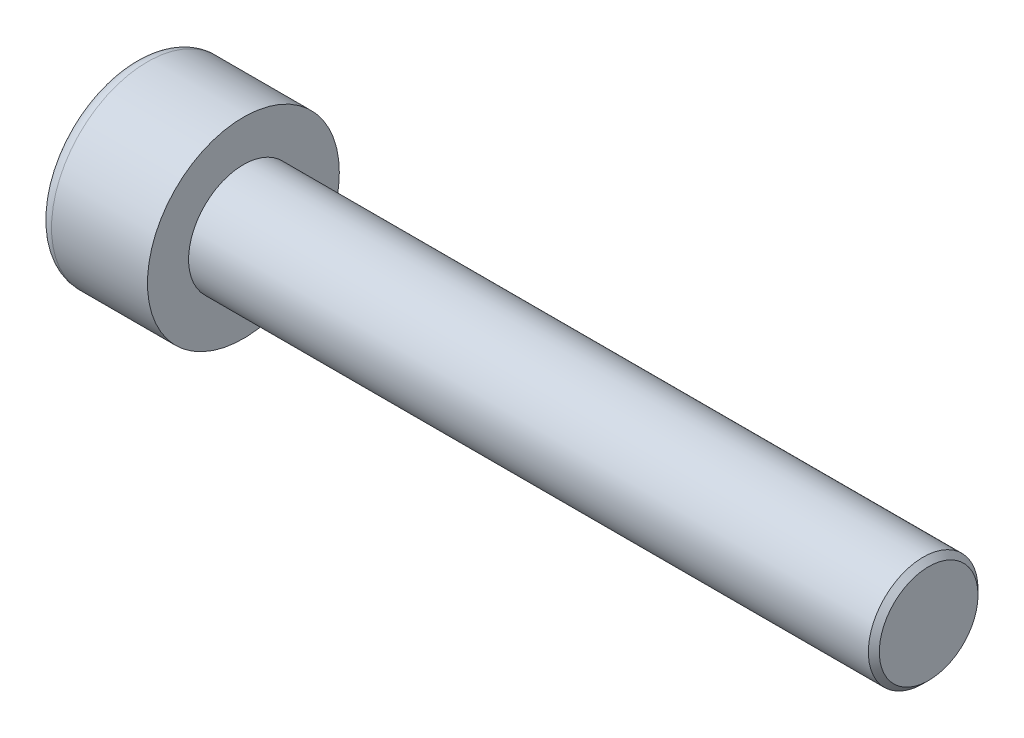
SolidWorks part; units mm, degrees
ref_plane "Front" through (0, 0, 0) normal (0, 0, 1) x (1, 0, 0)
ref_plane "Top" through (0, 0, 0) normal (0, 1, 0) x (1, 0, 0)
ref_plane "Right" through (0, 0, 0) normal (1, 0, 0) x (0, 0, -1)
sketch "Sketch1" plane through (0, 0, 0) normal (1, 0, 0) x (0, 0, -1)
  circle A0 centre (0, 0) radius 3.5
  dimension "dk" = 7
extrude "BaseHead" add sketch "Sketch1" along normal blind 4
sketch "Sketch2" plane through (4, 0, 0) normal (1, 0, 0) x (0, 0, -1)
  circle A0 centre (0, 0) radius 2
  dimension "d" = 4
extrude "BaseBody" add sketch "Sketch2" along normal blind 25
cosmetic thread "ThreadCosmetic1" parameters "b"=25, "D2"=3.242
sketch "Sketch3" plane through (0, 0, 0) normal (1, 0, 0) x (0, 0, -1)
  line L1 (1.7321, 0) -> (0.866, 1.5)
  line L2 (0.866, 1.5) -> (-0.866, 1.5)
  line L3 (-0.866, 1.5) -> (-1.7321, 0)
  line L4 (-1.7321, 0) -> (-0.866, -1.5)
  line L5 (-0.866, -1.5) -> (0.866, -1.5)
  line L6 (0.866, -1.5) -> (1.7321, 0)
  circle A0 centre (0, 0) radius 1.5 construction
  dimension "s" = 3
  dimension "e" = 3.4641
extrude "HexagonSocket" cut sketch "Sketch3" along normal blind 2
sketch "Sketch4" plane through (-4.1961, 0.75, 0) normal (0, 0, 1) x (-1, 0, 0)
  line L0 (-6.1961, 2.25) -> (-7.0622, 0.75)
  line L2 (-7.0622, 0.75) -> (-6.1961, 0.75)
  line L3 (-6.1961, 0.75) -> (-6.1961, 2.25)
  line L4 (-5.0351, 0.75) -> (0.839, 0.75) construction
  line L5 (-33.1961, 0.75) -> (-8.1961, 0.75) construction
  line L6 (-8.1961, 0.75) -> (-4.1961, 0.75) construction
  dimension "m" = 60
revolve "Cut-Revolve1" cut sketch "Sketch4" angle 360 about L4
fillet "HeadFillet" [suppressed] radius 0.2
fillet "TopFillet" radius 0.5 1 edges at (0, 0, -3.5)
chamfer "Chamfer1" distance 0.2 angle 45 1 edges at (29, 0, -2)
sketch "Sketch5" plane through (0, 0, 0) normal (0, 0, 1) x (1, 0, 0)
  line L0 (28.8, 1.6718) -> (28.9895, 2)
  line L1 (28.9895, 2) -> (28.9895, 2.379)
  line L2 (28.9895, 2.379) -> (28.6105, 2.379)
  line L3 (28.6105, 2.379) -> (28.6105, 2)
  line L4 (28.6105, 2) -> (28.8, 1.6718)
  line L5 (0, 0) -> (7.8886, 0) construction
  line L6 (28.8, -2) -> (28.8, 2) construction
  dimension "D1" = 4
  dimension "D2" = 0.379
revolve "Cut-Revolve10" [suppressed] cut sketch "Sketch5" angle 360 about L5
pattern_linear "LPattern10" [suppressed] count 55 spacing 0.4548 along (1, 0, 0)
equation "\"r1@TopFillet\" = \"d@Sketch2\" / 8"
equation "\"D1@Chamfer1\" = \"r@HeadFillet\""
equation "\"D1@Sketch5\" = \"d@Sketch2\""
equation "\"D2@Sketch5\" =  ( \"d@Sketch2\" - \"D2@ThreadCosmetic1\" )  / 2"
equation "\"D3@LPattern10\" = \"D2@Sketch5\" * 1.2"
equation "\"D1@LPattern10\" = \"b@ThreadCosmetic1\" / \"D3@LPattern10\""
